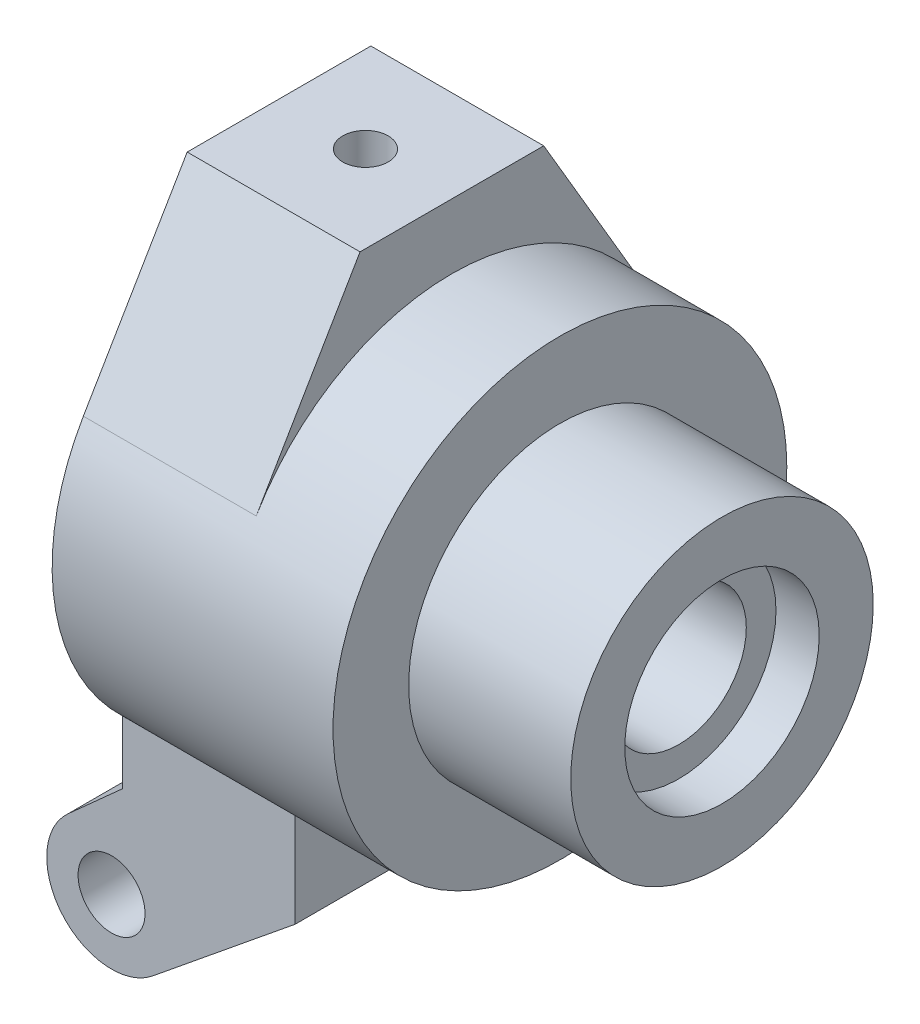
SolidWorks part; units mm, degrees
material "7050-T73510"
ref_plane "前视基准面" through (0, 0, 0) normal (0, 0, 1) x (1, 0, 0)
ref_plane "上视基准面" through (0, 0, 0) normal (0, 1, 0) x (1, 0, 0)
ref_plane "右视基准面" through (0, 0, 0) normal (1, 0, 0) x (0, 0, -1)
sketch "草图1" plane through (0, 0, 0) normal (1, 0, 0) x (0, 0, -1)
  circle A0 centre (0, 0) radius 21
  dimension "D1" = 42
extrude "凸台-拉伸1" add sketch "草图1" along normal blind 26
sketch "草图2" plane through (26, 0, 0) normal (1, 0, 0) x (0, 0, -1)
  circle A0 centre (0, 0) radius 14
  dimension "D1" = 28
extrude "凸台-拉伸2" add sketch "草图2" along normal blind 15
sketch "草图4" plane through (0, 0, 0) normal (-1, 0, 0) x (0, 0, 1)
  line L0 (-8.5, 27) -> (8.5, 27)
  line L1 (8.5, 27) -> (18.1096, 10.6322)
  line L2 (-8.5, 27) -> (-18.1096, 10.6322)
  line L3 (0, 27) -> (0, 0) construction
  circle A0 centre (0, 0) radius 21 construction
  circle A2 centre (0, 0) radius 21
  circle A3 centre (0, 0) radius 21
  point P3 (0, 27)
  circle M6 centre (0, 0) radius 21
  dimension "D1" = 17
  dimension "D2" = 27
  dimension "D3" = 0
extrude "凸台-拉伸3" add sketch "草图4" against normal blind 16 contours L3 L0 L2 A3 | L0 L3 L1 M6
sketch "草图5" plane through (0, 0, 0) normal (0, 0, 1) x (1, 0, 0)
  line L0 (0, -14) -> (0, -21.0414)
  line L1 (0, 10.6322) -> (0, -21) construction
  line L2 (0, -21.0414) -> (-5.0071, -25.5342)
  line L3 (16, -14) -> (16, -23.8968)
  line L4 (16, -23.8968) -> (2.7881, -34.653)
  line L5 (0, -14) -> (16, -14)
  line L6 (-7, -30) -> (-1, -30)
  circle A0 centre (-1, -30) radius 6
  circle A1 centre (-1, -30) radius 3.1
  dimension "D3" = 12
  dimension "D6" = 6.2
  dimension "D1" = 16
  dimension "D2" = 14
  dimension "D4" = 23
  dimension "D5" = 30
extrude "凸台-拉伸4" add sketch "草图5" along normal mid plane 29
sketch "草图6" plane through (0, 0, 0) normal (-1, 0, 0) x (0, 0, 1)
  circle A0 centre (0, 0) radius 17
  dimension "D1" = 34
extrude "切除-拉伸2" cut sketch "草图6" against normal blind 16
sketch "草图7" plane through (16, 0, 0) normal (-1, 0, 0) x (0, 0, 1)
  circle A0 centre (0, 0) radius 9
  dimension "D1" = 18
extrude "切除-拉伸3" cut sketch "草图7" against normal blind 4
sketch "草图8" plane through (20, 0, 0) normal (-1, 0, 0) x (0, 0, 1)
  circle A0 centre (0, 0) radius 6.25
  dimension "D1" = 12.5
extrude "切除-拉伸4" cut sketch "草图8" against normal through all
sketch "草图9" plane through (41, 0, 0) normal (1, 0, 0) x (0, 0, -1)
  circle A0 centre (0, 0) radius 9
  dimension "D1" = 18
extrude "切除-拉伸5" cut sketch "草图9" against normal blind 4
sketch "草图10" plane through (0, 27, 0) normal (0, 1, 0) x (1, 0, 0)
  circle A0 centre (8, 0) radius 1.75
  dimension "D1" = 3.5
  dimension "D2" = 8
extrude "切除-拉伸6" cut sketch "草图10" against normal up to surface (10.0903 mm away)
hole_wizard "M5 螺纹孔1" positions "3D草图2" profile "草图12" tap size "M5" standard "GB"
sketch3d "3D草图2"
  line L0 (8, 16.9097, 0) -> (8, 27, 0) construction
  point P0 (8, 27, 0)
sketch "草图12" plane through (8, 27, 0) normal (1, 0, 0) x (0, 0, 1)
  line L0 (0, 0) -> (0, 45.2608)
  line L1 (0, 45.2608) -> (2.1, 43.999)
  line L2 (2.1, 43.999) -> (2.1, 0)
  line L5 (2.1, 0) -> (0, 0)
  line L10 (0, 45.2608) -> (-2.1, 43.999) construction
  line L11 (0, -6.35) -> (0, 107.95) construction
  dimension "螺纹孔钻头直径" = 4.2
  dimension "螺纹孔钻头深度" = 43.999
  dimension "导头角度" = 118
cosmetic thread "孔螺蚊线1" parameters "D1"=10, "D2"=5
